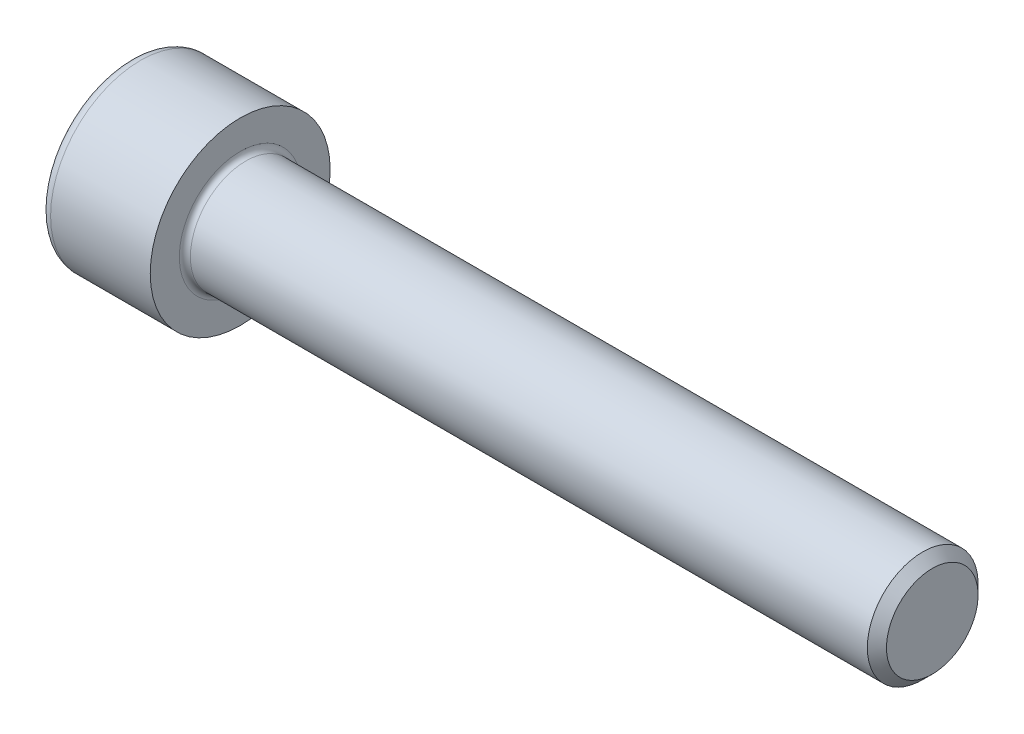
SolidWorks part; units mm, degrees
revolve "Base-Revolve" add sketch "BodySke"
sketch "BodySke" plane through (0, 0, 0) normal (0, 0, 1) x (1, 0, 0)
  line L0 (0, 0) -> (0, 6.5)
  line L1 (0, 6.5) -> (8, 6.5)
  line L2 (8, 6.5) -> (8, 4)
  line L3 (8, 4) -> (57.3095, 4)
  line L4 (58, 3.3095) -> (58, 0)
  line L5 (58, 0) -> (0, 0)
  line L6 (-31.75, 0) -> (127, 0) construction
  line L8 (58, 3.3095) -> (57.3095, 4)
  line L10 (58, -3.3095) -> (57.3095, -4) construction
  line L11 (9.25, 9.525) -> (9.25, 3.175) construction
  line L12 (30, 9.525) -> (30, 3.175) construction
  line L13 (-2, 9.525) -> (-2, 3.175) construction
  dimension "Body_ch_ang" = 45
  dimension "Thread_length" = 60
cosmetic thread "ThreadCosmetic"
fillet "Fillet1" radius 0.4 1 edges at (8, 0, 4)
fillet "Fillet2" radius 0.8 1 edges at (0, 0, 6.5)
material "304 Stainless Steel"
ref_plane "Plane1" through (0, 0, 0) normal (0, 0, 1) x (1, 0, 0)
ref_plane "Plane2" through (0, 0, 0) normal (0, 1, 0) x (1, 0, 0)
ref_plane "Plane3" through (0, 0, 0) normal (1, 0, 0) x (0, 0, -1)
sketch "Sketch2" plane through (0, 0, 0) normal (0, 0, 1) x (1, 0, 0)
  line L0 (0, 3.01) -> (4, 3.01)
  line L1 (4, 3.01) -> (5.7378, 0)
  line L2 (-31.75, 0) -> (127, 0) construction
  line L3 (5.7378, 0) -> (0, 0)
  line L4 (0, 0) -> (0, 3.01)
  line L6 (0, 0) -> (47.625, 0) construction
  dimension "D2" = 60
revolve "Hex-PreBroach" cut sketch "Sketch2" angle 360 about L6
sketch "Sketch3" plane through (0, 0, 0) normal (-1, 0, 0) x (0, 0.5, 0.866)
  line L0 (1.7378, 3.01) -> (-1.7378, 3.01)
  line L1 (-1.7378, 3.01) -> (-3.4756, 0)
  line L2 (1.7378, 3.01) -> (3.4756, 0)
  line L3 (1.7378, -3.01) -> (3.4756, 0)
  line L4 (1.7378, -3.01) -> (-1.7378, -3.01)
  line L5 (-1.7378, -3.01) -> (-3.4756, 0)
extrude "Hex" cut sketch "Sketch3" against normal blind 4
sketch "ThdSchSke" plane through (0, 0, 0) normal (0, 0, 1) x (1, 0, 0)
  line L0 (30, -3.3095) -> (29.5165, -4)
  line L1 (30, -3.3095) -> (30.4835, -4)
  line L2 (30.4835, -4) -> (30.4835, -5)
  line L3 (-3.175, 0) -> (5.1513, 0) construction
  line L4 (0, 5.7) -> (0, -5.7) construction
  line L5 (30.4835, -5) -> (29.5165, -5)
  line L6 (29.5165, -5) -> (29.5165, -4)
revolve "ThreadSchematic" [suppressed] cut sketch "ThdSchSke" angle 360 about L3
pattern_linear "ThdSchPat" [suppressed]
equation "\"D2@Sketch3\" = \"Hex_size@Sketch3\" / 2"
equation "\"D1@Sketch3\" = \"Hex_size@Sketch3\" / 2"
equation "\"D1@Sketch2\" = \"Hex_size@Sketch3\" / 2"
equation "\"Thread_minor@ThreadCosmetic\"  =  \"Minor_dia@BodySke\""
equation "\"Depth@Sketch2\" =  \"Key_eng@Hex\""
equation "\"Thread_length@ThreadCosmetic\" = ((sgn( (\"Length@BodySke\" - \"Advance@BodySke\" * 3.0) - \"Thread_nom@BodySke\" )-1)*( (\"Length@BodySke\" - \"Advance@BodySke\" * 3.0) - \"Thread_nom@BodySke\" ))/-2+ \"Thread_nom@BodySke\""
equation "\"Thread_minor@ThdSchSke\" = \"Minor_dia@BodySke\""
equation "\"Diameter@ThdSchSke\" = \"Diameter@BodySke\""
equation "\"Overcut@ThdSchSke\" = \"Diameter@BodySke\" * 1.25"
equation "\"Start@ThdSchSke\" = \"Head_ht@BodySke\" + \"Length@BodySke\" - \"Thread_length@ThreadCosmetic\"  '---Non-countersunk---"
equation "\"Num_threads@ThdSchPat\" = int( \"Thread_length@ThreadCosmetic\" / \"Advance@BodySke\" + 0.999 )  + 1"
equation "\"Advance@ThdSchPat\" = \"Thread_length@ThreadCosmetic\" /  (\"Num_threads@ThdSchPat\" - 1) 'relax it"
equation "\"Num_threads@ThdSchPat\" = \"Num_threads@ThdSchPat\" - sgn( \"Num_threads@ThdSchPat\" - 1) '---chamfered tips only---"
